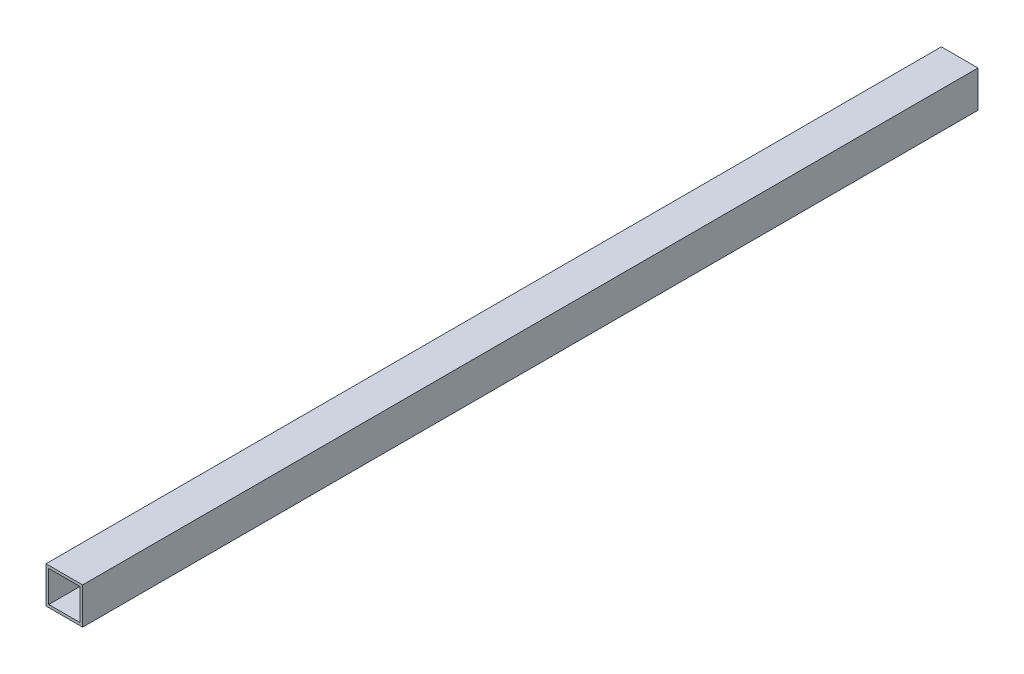
SolidWorks part; units mm, degrees
ref_plane "Alzado" through (0, 0, 0) normal (0, 0, 1) x (1, 0, 0)
ref_plane "Planta" through (0, 0, 0) normal (0, 1, 0) x (1, 0, 0)
ref_plane "Vista lateral" through (0, 0, 0) normal (1, 0, 0) x (0, 0, -1)
sketch "Croquis1" plane through (0, 0, 0) normal (0, 0, 1) x (1, 0, 0)
  line L1 (-6.75, 17.5) -> (6.75, 17.5)
  line L2 (-6.75, 17.5) -> (-6.75, 4)
  line L3 (-6.75, 4) -> (6.75, 4)
  line L4 (6.75, 17.5) -> (6.75, 4)
  line L5 (-5.75, 16.5) -> (5.75, 16.5)
  line L6 (-5.75, 16.5) -> (-5.75, 5)
  line L7 (-5.75, 5) -> (5.75, 5)
  line L8 (5.75, 16.5) -> (5.75, 5)
  dimension "D1" = 1
  dimension "D2" = 1
  dimension "D3" = 1
  dimension "D4" = 1
extrude "Saliente-Extruir1" add sketch "Croquis1" along normal blind 330 from offset 80
